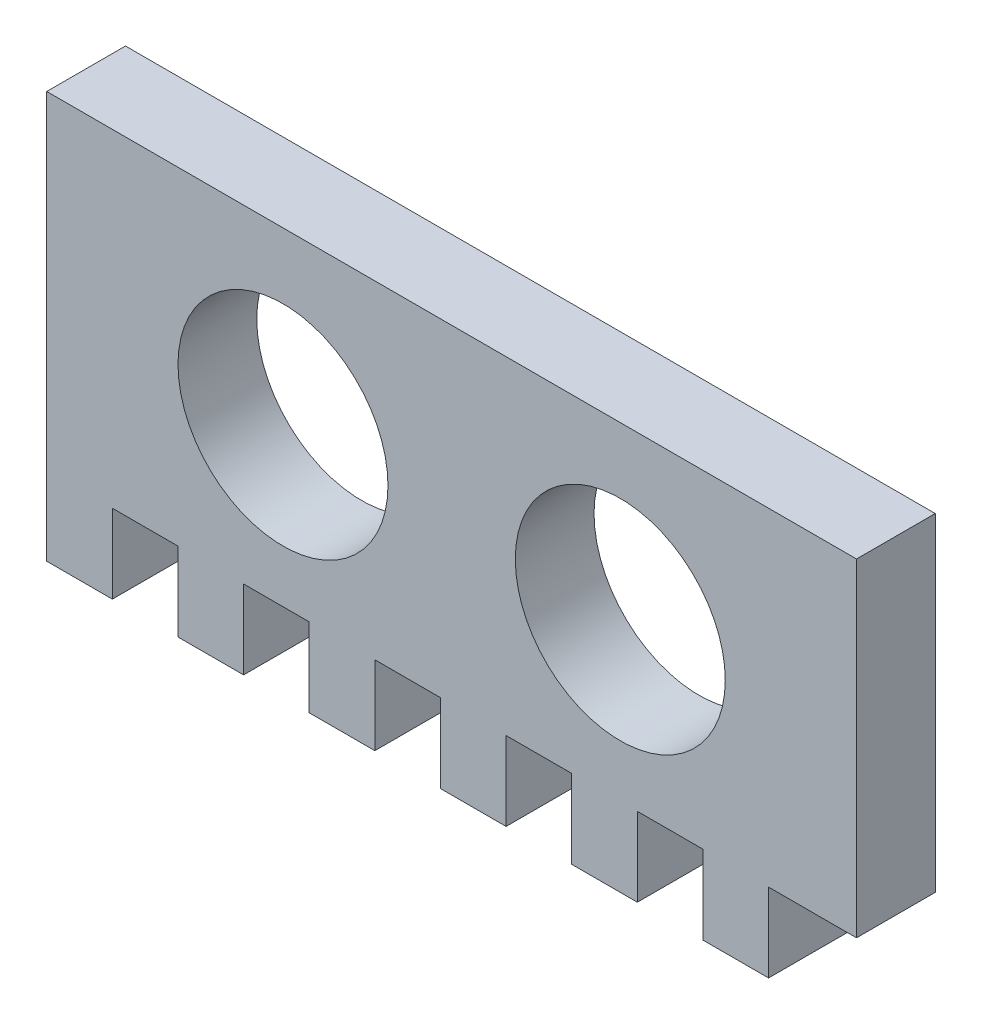
SolidWorks part; units mm, degrees
ref_plane "Plan de face" through (0, 0, 0) normal (0, 0, 1) x (1, 0, 0)
ref_plane "Plan de dessus" through (0, 0, 0) normal (0, 1, 0) x (1, 0, 0)
ref_plane "Plan de droite" through (0, 0, 0) normal (1, 0, 0) x (0, 0, -1)
sketch "Esquisse1" plane through (0, 0, 0) normal (0, 0, 1) x (1, 0, 0)
  line L0 (0, 0) -> (0, 31)
  line L1 (0, 31) -> (61.7, 31)
  line L2 (61.7, 31) -> (61.7, 6)
  line L3 (0, 0) -> (5, 0)
  line L4 (5, 0) -> (5, 6)
  line L5 (5, 6) -> (10, 6)
  line L6 (10, 6) -> (10, 0)
  line L7 (10, 0) -> (15, 0)
  line L8 (15, 0) -> (15, 6)
  line L9 (15, 6) -> (20, 6)
  line L10 (20, 6) -> (20, 0)
  line L11 (20, 0) -> (25, 0)
  line L12 (25, 0) -> (25, 6)
  line L13 (25, 6) -> (30, 6)
  line L14 (30, 6) -> (30, 0)
  line L15 (30, 0) -> (35, 0)
  line L16 (35, 0) -> (35, 6)
  line L17 (35, 6) -> (40, 6)
  line L18 (40, 6) -> (40, 0)
  line L19 (40, 0) -> (45, 0)
  line L20 (45, 0) -> (45, 6)
  line L21 (45, 6) -> (50, 6)
  line L22 (50, 6) -> (50, 0)
  line L23 (50, 0) -> (55, 0)
  line L24 (55, 0) -> (55, 6)
  line L25 (55, 6) -> (61.7, 6)
  circle A0 centre (18, 18) radius 8
  circle A1 centre (43.7, 18) radius 8
  dimension "D1" = 16
  dimension "D2" = 16
  dimension "D3" = 25.7
  dimension "D4" = 18
  dimension "D9" = 12
  dimension "D10" = 13
  dimension "D5" = 18
  dimension "D6" = 5
  dimension "D7" = 5
  dimension "D11" = 6
extrude "Boss.-Extru.1" add sketch "Esquisse1" along normal blind 6
